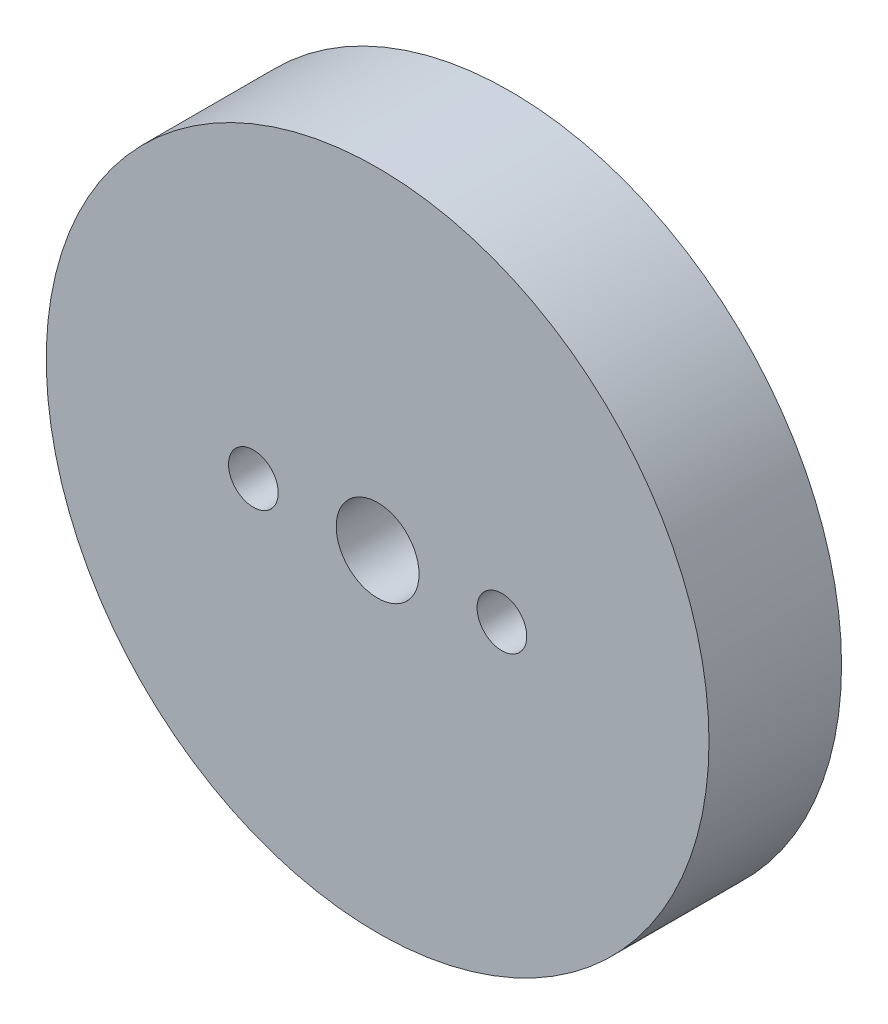
SolidWorks part; units mm, degrees
ref_plane "Front Plane" through (0, 0, 0) normal (0, 0, 1) x (1, 0, 0)
ref_plane "Top Plane" through (0, 0, 0) normal (0, 1, 0) x (1, 0, 0)
ref_plane "Right Plane" through (0, 0, 0) normal (1, 0, 0) x (0, 0, -1)
sketch "Sketch1" plane through (0, 0, 0) normal (0, 0, 1) x (1, 0, 0)
  circle A0 centre (0, 0) radius 20
  circle A1 centre (0, 0) radius 2.5
  circle A2 centre (7.5, 0) radius 1.5
  circle A3 centre (-7.5, 0) radius 1.5
extrude "Boss-Extrude3" add sketch "Sketch1" along normal blind 8
